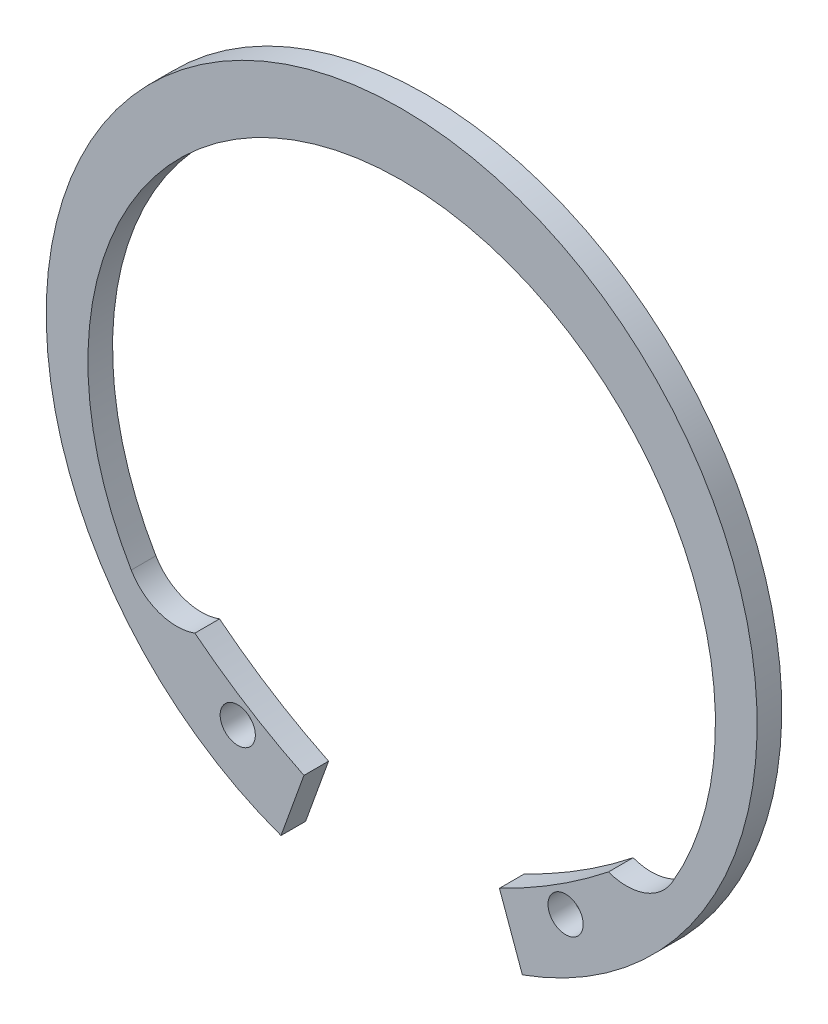
SolidWorks part; units mm, degrees
ref_plane "Front Plane" through (0, 0, 0) normal (0, 0, 1) x (1, 0, 0)
ref_plane "Top Plane" through (0, 0, 0) normal (0, 1, 0) x (1, 0, 0)
ref_plane "Right Plane" through (0, 0, 0) normal (1, 0, 0) x (0, 0, -1)
sketch "Sketch1" plane through (0, 0, 0) normal (0, 0, 1) x (1, 0, 0)
  line L0 (0, 25.25) -> (0, 20.85) construction
  line L1 (-21.0449, -13.9526) -> (-19.2113, -12.7369) construction
  line L2 (0, 0) -> (0, -25.25) construction
  line L3 (-6.4, -17.7303) -> (-8.5729, -23.7501) construction
  line L4 (-6.4, -17.7303) -> (-8.9, -17.7303) construction
  circle A0 centre (0, 0) radius 24.75 construction
  circle A1 centre (0, 0) radius 25.25 construction
  circle A2 centre (0, 0) radius 23.5 construction
  dimension "Ring OD" = 50.5
  dimension "For ID" = 47
  dimension "Maximum Section" = 4.4
  dimension "Maximum Lug Height" = 6.4
  dimension "Hole Diameter" = 2.5
  dimension "D2" = 2.2
  dimension "Gap Width" = 12.8
  dimension "D1" = 13.75
sketch "Sketch2" plane through (0, 0, 0) normal (1, 0, 0) x (0, 0, -1)
  line L0 (-0.925, 25.25) -> (0.925, 25.25) construction
  line L1 (-0.875, -25.25) -> (0.875, -25.25) construction
  point P3 (0, 25.25)
  point P7 (0, -25.25)
  point P8 (-0.875, -25.25)
  point P10 (0.875, -25.25)
  point P11 (-0.925, 25.25)
  point P12 (0.925, 25.25)
  dimension "For Groove Width" = 1.85
  dimension "Ring Thickness" = 1.75
sketch "Sketch3" plane through (0, 0, 0) normal (0, 0, 1) x (1, 0, 0)
  line L0 (-8.5729, -23.7501) -> (-6.9432, -19.2352)
  line L1 (-6.9432, -19.2352) -> (-14.6893, -14.3571)
  line L2 (0, 0) -> (-10.6453, -16.9038) construction
  line L3 (-19.2113, -12.7369) -> (19.2113, -12.7369) construction
  line L4 (0, 0) -> (0, -25.25) construction
  line L7 (-11.6445, -18.4904) -> (-10.6453, -16.9038) construction
  line L8 (0, 25.25) -> (0, 20.85) construction
  line L9 (6.9432, -19.2352) -> (14.6893, -14.3571)
  line L10 (8.5729, -23.7501) -> (6.9432, -19.2352)
  line L12 (-6.4, -17.7303) -> (-8.5729, -23.7501) construction
  arc A0 (-8.5729, -23.7501) -> (8.5729, -23.7501) centre (0, 0) cw
  circle A1 centre (0, 0) radius 25.25 construction
  arc A2 (-19.2113, -12.7369) -> (19.2113, -12.7369) centre (0, -1.4378) cw
  arc A3 (-19.2113, -12.7369) -> (-14.6893, -14.3571) centre (-15.9789, -10.8358) ccw
  circle A4 centre (-11.6445, -18.4904) radius 1.25
  circle A5 centre (0, 0) radius 23.05 construction
  arc A6 (19.2113, -12.7369) -> (14.6893, -14.3571) centre (15.9789, -10.8358) cw
  circle A7 centre (11.6445, -18.4904) radius 1.25
  point P3 (0, -12.7369)
  dimension "D1" = 2.5
  dimension "D5" = 3.75
  dimension "D2" = 4.375
  dimension "D3" = 4.8
  dimension "D4" = 1.875
extrude "Boss-Extrude1" add sketch "Sketch3" against normal up to vertex (0.875 mm away) and the other way up to vertex (0.875 mm away) up to point (0, -25.25, -0.875) other way up to point (0, -25.25, 0.875)
sketch "Sketch5" plane through (0, 0, 0) normal (0, 0, 1) x (1, 0, 0)
  line L1 (-14.6893, -14.3571) -> (0, 0)
  line L2 (0, 0) -> (-6.9432, -19.2352)
  line L3 (-6.9432, -19.2352) -> (-14.6893, -14.3571) construction
  arc A0 (-14.6893, -14.3571) -> (-6.9432, -19.2352) centre (11.4447, 18.5524) ccw
  arc A3 (-19.2113, -12.7369) -> (-14.6893, -14.3571) centre (-15.9789, -10.8358) ccw construction
  point P3 (-10.9495, -17.0077)
  dimension "D1" = 0.25
extrude "Cut-Extrude2" cut sketch "Sketch5" against normal through all both and the other way through all
mirror "Mirror1" about plane through (0, 0, 0) normal (1, 0, 0) of "Cut-Extrude2"
equation "\"D1@Sketch3\"=\"Hole Diameter@Sketch1\""
equation "\"D2@Sketch3\"=\"Hole Diameter@Sketch1\"*1.75"
equation "\"D2@Sketch1\"=\"Maximum Section@Sketch1\"*.5"
equation "\"Gap Width@Sketch1\" = \"Maximum Lug Height@Sketch1\" * 2"
equation "\"D3@Sketch3\" = \"Maximum Lug Height@Sketch1\" * .75"
equation "\"D4@Sketch3\"=\"Hole Diameter@Sketch1\"*.75"
equation "\"D1@Sketch1\"=\"Hole Diameter@Sketch1\"*5.5"
equation "\"D5@Sketch3\"=\"Hole Diameter@Sketch1\"*1.5"
